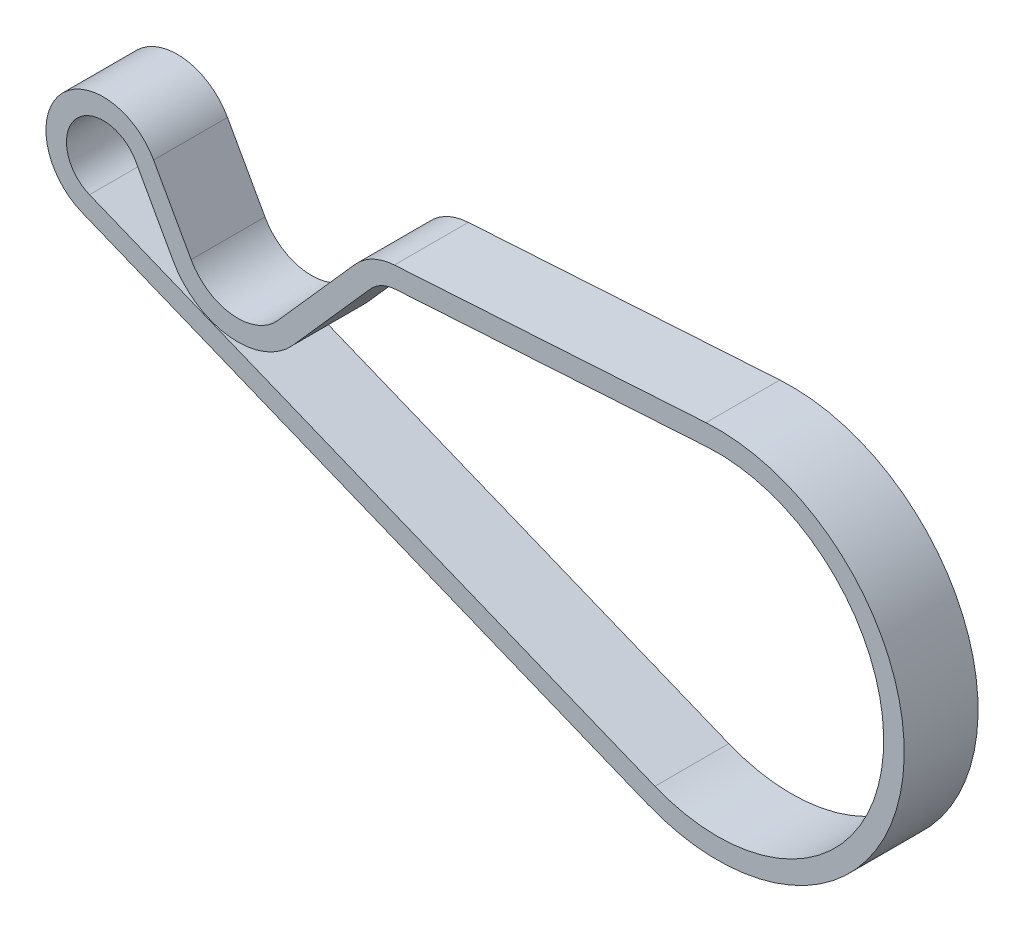
SolidWorks part; units mm, degrees
material "Beryllium"
ref_plane "Front Plane" through (0, 0, 0) normal (0, 0, 1) x (1, 0, 0)
ref_plane "Top Plane" through (0, 0, 0) normal (0, 1, 0) x (1, 0, 0)
ref_plane "Right Plane" through (0, 0, 0) normal (1, 0, 0) x (0, 0, -1)
sketch "Sketch1" plane through (0, 0, 0) normal (0, 0, 1) x (1, 0, 0)
  line L0 (23.1265, -71.6245) -> (60.7653, -29.13)
  line L1 (-45.4392, -33.2196) -> (-27.1854, -66.1125)
  line L2 (-74.2016, -65.6908) -> (201.3555, -177.5593)
  line L3 (228.3996, -12.0392) -> (76.5638, -21.4238)
  line L5 (-65.55, -44.38) -> (77.9826, -44.38) construction
  arc A0 (-45.4392, -33.2196) -> (-74.2016, -65.6908) centre (-65.55, -44.38) ccw
  arc A1 (201.3555, -177.5593) -> (228.3996, -12.0392) centre (233.7049, -97.8755) ccw
  arc A9 (76.5638, -21.4238) -> (60.7653, -29.13) centre (77.9826, -44.38) ccw
  arc A10 (-27.1854, -66.1125) -> (23.1265, -71.6245) centre (-0.0795, -51.0702) ccw
  point P2 (17.7027, -103.0014)
  point P7 (79.0846, 51.2318)
  point P10 (-27.8987, -2.393)
  dimension "D1" = 23
  dimension "D2" = 31
  dimension "D4" = 86
extrude "Extrude-Thin1" add sketch "Sketch1" along normal blind 28 and the other way blind 8 thin thin type mid plane wall 10
